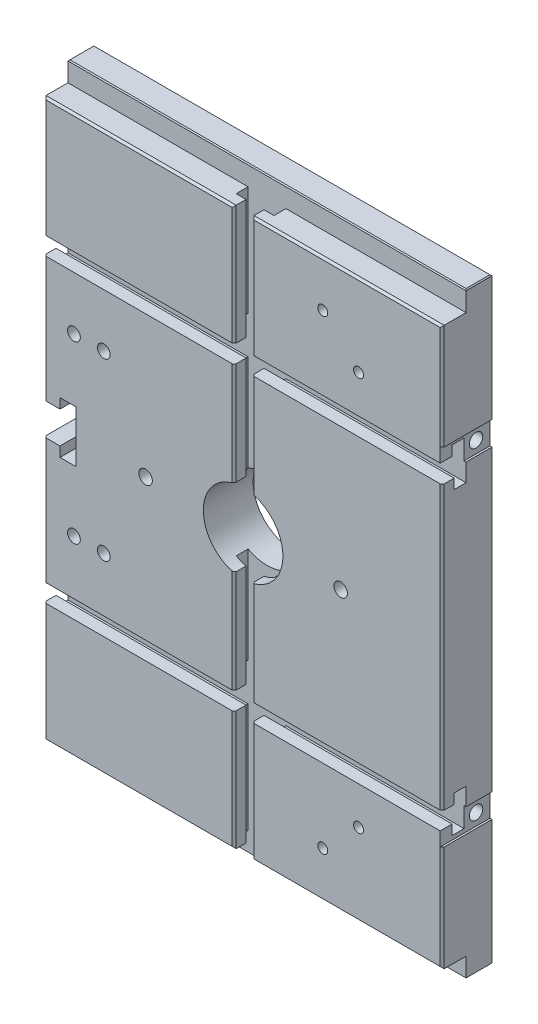
SolidWorks part; units mm, degrees
ref_plane "Front Plane" through (0, 0, 0) normal (0, 0, 1) x (1, 0, 0)
ref_plane "Top Plane" through (0, 0, 0) normal (0, 1, 0) x (1, 0, 0)
ref_plane "Right Plane" through (0, 0, 0) normal (1, 0, 0) x (0, 0, -1)
sketch "草图1" plane through (0, 0, 0) normal (0, 0, 1) x (1, 0, 0)
  line L1 (110, 500) -> (310, 500)
  line L2 (110, 500) -> (110, 200)
  line L3 (110, 200) -> (310, 200)
  line L4 (310, 500) -> (310, 200)
  dimension "D1" = 300
  dimension "D2" = 200
extrude "凸台-拉伸1" add sketch "草图1" along normal blind 25
sketch "草图2" plane through (110, 0, 0) normal (-1, 0, 0) x (0, 0, 1)
  line L1 (25, 500) -> (13, 500)
  line L2 (25, 500) -> (25, 490)
  line L3 (25, 490) -> (13, 490)
  line L4 (13, 500) -> (13, 490)
  line L5 (25, 200) -> (13, 200)
  line L6 (25, 200) -> (25, 210)
  line L7 (25, 210) -> (13, 210)
  line L8 (13, 200) -> (13, 210)
  dimension "D1" = 12
  dimension "D2" = 10
  dimension "D3" = 12
  dimension "D4" = 10
extrude "切除-拉伸1" cut sketch "草图2" against normal through all
sketch "草图3" plane through (0, 490, 0) normal (0, 1, 0) x (1, 0, 0)
  line L0 (310, -25) -> (110, -25) construction
  line L1 (205.5, -25) -> (214.5, -25)
  line L2 (205.5, -25) -> (205.5, -19)
  line L4 (214.5, -25) -> (214.5, -19)
  line L5 (310, -13) -> (110, -13) construction
  line L6 (110, -13) -> (110, -25) construction
  line L8 (214.5, -19) -> (219.5, -19)
  line L9 (200.5, -13) -> (219.5, -13)
  line L10 (200.5, -13) -> (200.5, -19)
  line L11 (200.5, -19) -> (205.5, -19)
  line L12 (219.5, -13) -> (219.5, -19)
  dimension "D1" = 9
  dimension "D2" = 95.5
  dimension "D3" = 5
  dimension "D4" = 5
  dimension "D5" = 6
extrude "切除-拉伸2" cut sketch "草图3" against normal through all
chamfer "倒角2" distance 0.5 angle 45 8 edges at (210, 200, 0) (110, 200, 6.5) (210, 200, 13) (310, 200, 6.5) (210, 500, 0) (310, 500, 6.5) (210, 500, 13) (110, 500, 6.5)
chamfer "倒角3" distance 1 angle 45 4 edges at (262.25, 490, 25) (262.25, 210, 25) (157.75, 210, 25) (157.75, 490, 25)
sketch "草图4" plane through (0, 0, 25) normal (0, 0, 1) x (1, 0, 0)
  line L0 (310, 490) -> (310, 210) construction
  line L2 (309.5, 200) -> (110.5, 200) construction
  circle A0 centre (210, 350) radius 20
  dimension "D1" = 40
  dimension "D2" = 100
  dimension "D3" = 150
extrude "切除-拉伸3" cut sketch "草图4" against normal through all
sketch "草图5" plane through (110, 0, 0) normal (-1, 0, 0) x (0, 0, 1)
  line L0 (25, 421) -> (25, 430)
  line L1 (25, 421) -> (19, 421)
  line L2 (25, 430) -> (19, 430)
  line L3 (19, 430) -> (19, 435)
  line L4 (13, 416) -> (13, 435)
  line L5 (13, 416) -> (19, 416)
  line L6 (19, 416) -> (19, 421)
  line L7 (13, 435) -> (19, 435)
  line L8 (25, 489) -> (25, 211) construction
  line L9 (0.5, 500) -> (12.5, 500) construction
  line L10 (0, 350) -> (60.2643, 350) construction
  line L11 (0, 499.5) -> (0, 200.5) construction
  line L12 (13, 265) -> (19, 265)
  line L13 (19, 284) -> (19, 279)
  line L14 (13, 284) -> (19, 284)
  line L15 (13, 284) -> (13, 265)
  line L16 (19, 270) -> (19, 265)
  line L17 (25, 270) -> (19, 270)
  line L18 (25, 279) -> (19, 279)
  line L19 (25, 279) -> (25, 270)
  dimension "D1" = 9
  dimension "D2" = 5
  dimension "D3" = 6
  dimension "D4" = 12
  dimension "D5" = 65
  dimension "D6" = 19
extrude "切除-拉伸4" cut sketch "草图5" against normal through all
hole_wizard "M8x1.25 螺纹孔1" positions "草图9" profile "草图8" tap size "M8x1.25" standard "Ansi Metric" end condition through all
sketch "草图9" plane through (0, 0, 25) normal (0, 0, 1) x (1, 0, 0)
  arc A0 (204.5, 369.2289) -> (204.5, 330.7711) centre (210, 350) ccw construction
  point P0 (161, 350)
  point P10 (210, 399)
  point P11 (259, 350)
  point P12 (210, 301)
  dimension "D1" = 49
  dimension "D2" = 4
sketch "草图8" plane through (161, 350, 25) normal (1, 0, 0) x (0, -1, 0)
  line L0 (0, 0) -> (0, 25)
  line L1 (0, 25) -> (3.4, 25)
  line L2 (3.4, 25) -> (3.4, 0)
  line L5 (3.4, 0) -> (0, 0)
  line L11 (0, -6.35) -> (0, 107.95) construction
  dimension "通孔螺纹孔钻头直径" = 6.8
  dimension "通孔螺纹孔钻头深度" = 25
cosmetic thread "孔螺蚊线2" parameters "D2"=8
cosmetic thread "孔螺蚊线3" parameters "D2"=8
cosmetic thread "孔螺蚊线4" parameters "D2"=8
cosmetic thread "孔螺蚊线5" parameters "D2"=8
hole_wizard "M6 凹头盖螺钉的柱形沉头孔1" positions "草图11" profile "草图10" counterbore size "M6" standard "Ansi Metric" end condition through all
sketch "草图11" plane through (0, 0, 0) normal (0, 0, -1) x (-1, 0, 0)
  line L0 (-110, 499.5) -> (-110, 200.5) construction
  line L2 (-310, 200.5) -> (-110, 200.5) construction
  point P0 (-125, 394.25)
  point P2 (-140, 394.25)
  point P4 (-140, 306.25)
  point P6 (-125, 306.25)
  dimension "D1" = 88
  dimension "D2" = 88
  dimension "D3" = 15
  dimension "D4" = 15
  dimension "D5" = 15
  dimension "D6" = 15
  dimension "D7" = 105.75
  dimension "D8" = 105.75
sketch "草图10" plane through (125, 394.25, 0) normal (1, 0, 0) x (0, 1, 0)
  line L0 (0, 0) -> (0, 25)
  line L1 (0, 25) -> (3.2, 25)
  line L3 (3.2, 25) -> (3.2, 6)
  line L4 (3.2, 6) -> (5.5, 6)
  line L5 (5.5, 6) -> (5.5, 0)
  line L7 (5.5, 0) -> (0, 0)
  line L11 (0, -6.35) -> (0, 107.95) construction
  dimension "通孔孔直径" = 6.4
  dimension "通孔孔深度" = 25
  dimension "柱形沉头孔直径" = 11
  dimension "柱形沉头孔深度" = 6
sketch "草图12" plane through (0, 0, 25) normal (0, 0, 1) x (1, 0, 0)
  line L0 (310, 421) -> (310, 279) construction
  line L1 (310, 425) -> (309, 425)
  line L2 (310, 425) -> (310, 437)
  line L3 (310, 437) -> (309, 437)
  line L4 (309, 425) -> (309, 437)
  line L5 (101.5425, 350) -> (319.6733, 350) construction
  line L6 (309, 275) -> (309, 263)
  line L7 (310, 263) -> (309, 263)
  line L8 (310, 275) -> (310, 263)
  line L9 (310, 275) -> (309, 275)
  dimension "D1" = 12
  dimension "D2" = 1
  dimension "D3" = 75
extrude "切除-拉伸5" cut sketch "草图12" against normal through all
hole_wizard "M8x1.25 螺纹孔2" positions "草图14" profile "草图13" tap size "M8x1.25" standard "Ansi Metric"
sketch "草图14" plane through (309, 0, 0) normal (1, 0, 0) x (0, 0, -1)
  line L0 (0, 437) -> (0, 425) construction
  line L1 (0, 275) -> (0, 263) construction
  point P0 (-7, 431)
  point P2 (-7, 269)
  dimension "D1" = 7
  dimension "D2" = 7
sketch "草图13" plane through (309, 431, 7) normal (0, 1, 0) x (0, 0, -1)
  line L0 (0, 0) -> (0, 24.2929)
  line L1 (0, 24.2929) -> (3.4, 22.25)
  line L2 (3.4, 22.25) -> (3.4, 0)
  line L5 (3.4, 0) -> (0, 0)
  line L10 (0, 24.2929) -> (-3.4, 22.25) construction
  line L11 (0, -6.35) -> (0, 107.95) construction
  dimension "螺纹孔钻头直径" = 6.8
  dimension "螺纹孔钻头深度" = 22.25
  dimension "导头角度" = 118
cosmetic thread "孔螺蚊线6" parameters "D1"=16, "D2"=8
cosmetic thread "孔螺蚊线7" parameters "D1"=16, "D2"=8
hole_wizard "M6x1.0 螺纹孔1" positions "草图16" profile "草图15" tap size "M6x1.0" standard "Ansi Metric"
sketch "草图16" plane through (110, 0, 0) normal (-1, 0, 0) x (0, 0, 1)
  line L0 (0, 499.5) -> (0, 200.5) construction
  line L1 (0.5, 500) -> (12.5, 500) construction
  point P0 (7, 380)
  point P2 (7, 320)
  dimension "D1" = 60
  dimension "D2" = 7
  dimension "D3" = 7
  dimension "D4" = 120
sketch "草图15" plane through (110, 380, 7) normal (0, 1, 0) x (0, 0, 1)
  line L0 (0, 0) -> (0, 18.5022)
  line L1 (0, 18.5022) -> (2.5, 17)
  line L2 (2.5, 17) -> (2.5, 0)
  line L5 (2.5, 0) -> (0, 0)
  line L10 (0, 18.5022) -> (-2.5, 17) construction
  line L11 (0, -6.35) -> (0, 107.95) construction
  dimension "螺纹孔钻头直径" = 5
  dimension "螺纹孔钻头深度" = 17
  dimension "导头角度" = 118
cosmetic thread "孔螺蚊线8" parameters "D1"=12, "D2"=6
cosmetic thread "孔螺蚊线9" parameters "D1"=12, "D2"=6
hole_wizard "M6x1.0 螺纹孔2" positions "草图18" profile "草图17" tap size "M6x1.0" standard "Ansi Metric" end condition through all
sketch "草图18" plane through (0, 0, 25) normal (0, 0, 1) x (1, 0, 0)
  circle A0 centre (210, 399) radius 3.4 construction
  arc A1 (215.5, 330.7711) -> (215.5, 369.2289) centre (210, 350) ccw construction
  arc A2 (204.5, 369.2289) -> (204.5, 330.7711) centre (210, 350) ccw construction
  point P0 (250, 467)
  point P2 (268, 449)
  point P4 (250, 233)
  point P6 (268, 251)
  dimension "D1" = 58
  dimension "D2" = 58
  dimension "D3" = 40
  dimension "D4" = 40
  dimension "D5" = 99
  dimension "D6" = 99
  dimension "D7" = 117
  dimension "D8" = 117
sketch "草图17" plane through (250, 467, 25) normal (1, 0, 0) x (0, -1, 0)
  line L0 (0, 0) -> (0, 25)
  line L1 (0, 25) -> (2.5, 25)
  line L2 (2.5, 25) -> (2.5, 0)
  line L5 (2.5, 0) -> (0, 0)
  line L11 (0, -6.35) -> (0, 107.95) construction
  dimension "通孔螺纹孔钻头直径" = 5
  dimension "通孔螺纹孔钻头深度" = 25
cosmetic thread "孔螺蚊线10" parameters "D2"=6
cosmetic thread "孔螺蚊线11" parameters "D2"=6
cosmetic thread "孔螺蚊线12" parameters "D2"=6
cosmetic thread "孔螺蚊线13" parameters "D2"=6
sketch "草图19" plane through (0, 0, 25) normal (0, 0, 1) x (1, 0, 0)
  line L0 (110, 279) -> (110, 421) construction
  line L1 (110, 358) -> (118, 358)
  line L2 (110, 358) -> (110, 342)
  line L3 (110, 342) -> (118, 342)
  line L4 (118, 358) -> (118, 363)
  line L5 (110.5, 500) -> (309.5, 500) construction
  line L6 (118, 337) -> (126, 337)
  line L7 (118, 337) -> (118, 342)
  line L8 (118, 363) -> (126, 363)
  line L9 (126, 337) -> (126, 363)
  dimension "D1" = 8
  dimension "D2" = 8
  dimension "D3" = 16
  dimension "D4" = 5
  dimension "D5" = 5
  dimension "D6" = 142
extrude "切除-拉伸6" cut sketch "草图19" against normal through all
